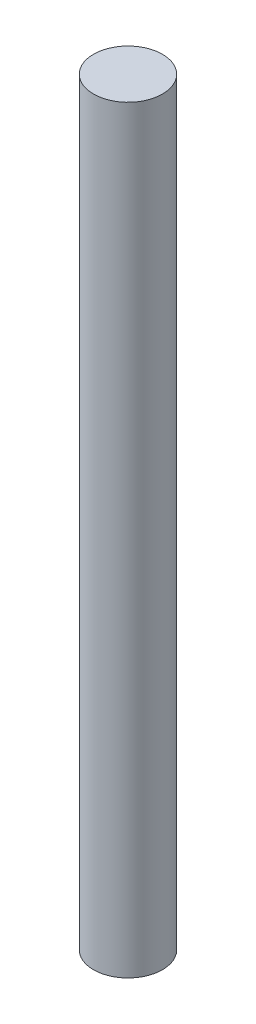
SolidWorks part; units mm, degrees
ref_plane "Front Plane" through (0, 0, 0) normal (0, 0, 1) x (1, 0, 0)
ref_plane "Top Plane" through (0, 0, 0) normal (0, 1, 0) x (1, 0, 0)
ref_plane "Right Plane" through (0, 0, 0) normal (1, 0, 0) x (0, 0, -1)
sketch "Sketch1" plane through (0, 0, 0) normal (0, 1, 0) x (1, 0, 0)
  circle A0 centre (0, 0) radius 2.5
  dimension "D1" = 5
extrude "Boss-Extrude1" add sketch "Sketch1" along normal blind 55
